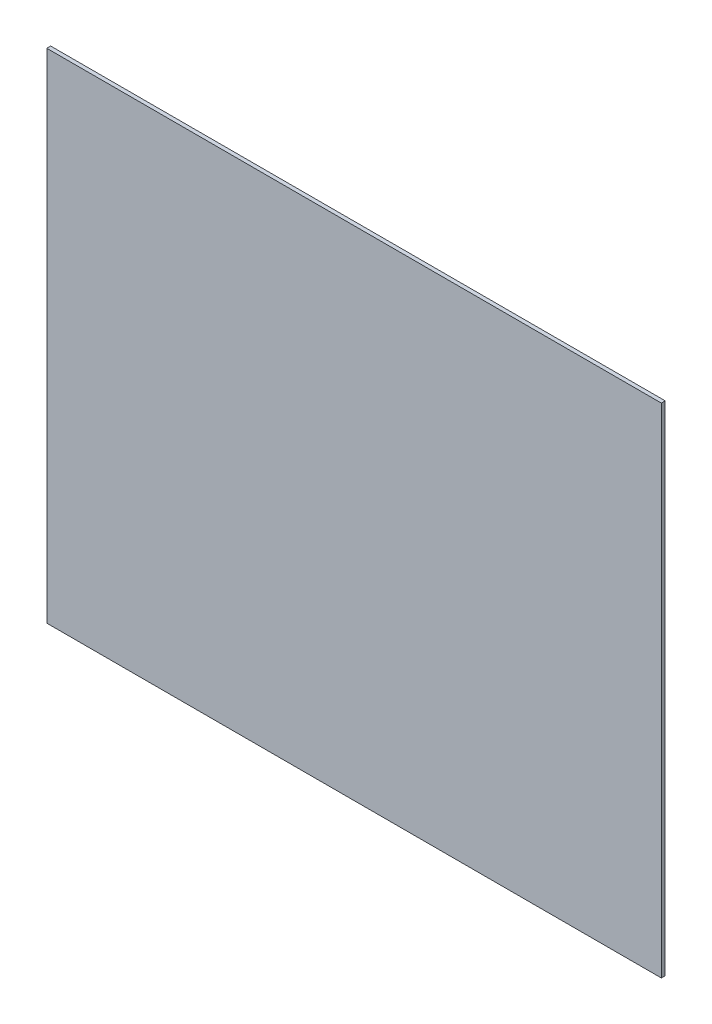
SolidWorks part; units mm, degrees
ref_plane "Front Plane" through (0, 0, 0) normal (0, 0, 1) x (1, 0, 0)
ref_plane "Top Plane" through (0, 0, 0) normal (0, 1, 0) x (1, 0, 0)
ref_plane "Right Plane" through (0, 0, 0) normal (1, 0, 0) x (0, 0, -1)
sketch "Sketch1" plane through (0, 0, 0) normal (0, 0, 1) x (1, 0, 0)
  line L0 (-243.8408, 0) -> (243.8408, 0) construction
  line L1 (0, -216.5112) -> (0, 216.5112) construction
  line L2 (-125.4125, -167.3179) -> (-125.4125, 167.3179) construction
  line L3 (125.4125, -167.3179) -> (125.4125, 167.3179) construction
  line L5 (-125.4125, -50.8) -> (125.4125, -50.8)
  line L6 (-125.4125, -50.8) -> (-125.4125, 152.4)
  line L7 (-125.4125, 152.4) -> (125.4125, 152.4)
  line L8 (125.4125, -50.8) -> (125.4125, 152.4)
  line L9 (-125.4125, -50.8) -> (125.4125, 152.4) construction
  line L10 (-125.4125, 152.4) -> (125.4125, -50.8) construction
  point P4 (0, 0)
  point P8 (0, 0)
  point P11 (-125.4125, 0)
  point P13 (0, 50.8)
  dimension "D1" = 125.4125
  dimension "D2" = 250.825
  dimension "D3" = 152.4
  dimension "D4" = 203.2
extrude "Boss-Extrude1" add sketch "Sketch1" along normal mid plane 1.5875
